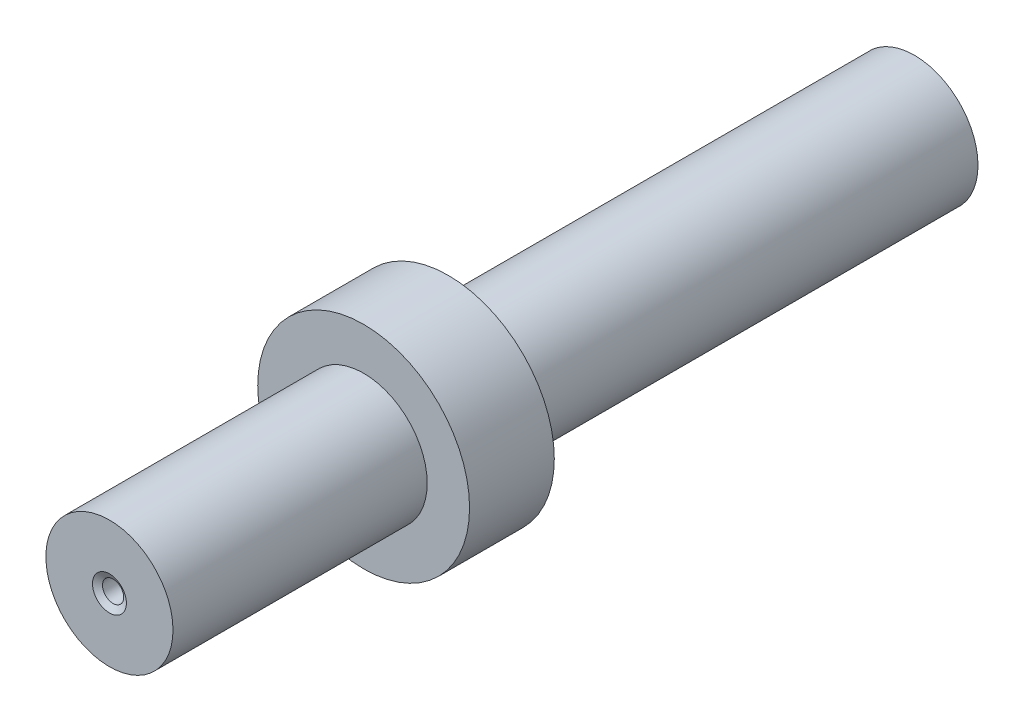
SolidWorks part; units mm, degrees
material "Chrome Stainless Steel"
ref_plane "Front Plane" through (0, 0, 0) normal (0, 0, 1) x (1, 0, 0)
ref_plane "Top Plane" through (0, 0, 0) normal (0, 1, 0) x (1, 0, 0)
ref_plane "Right Plane" through (0, 0, 0) normal (1, 0, 0) x (0, 0, -1)
sketch "Sketch1" plane through (0, 0, 0) normal (0, 0, 1) x (1, 0, 0)
  circle A0 centre (0, 0) radius 12.5
  dimension "D1" = 25
extrude "25mm dia" add sketch "Sketch1" along normal blind 10
sketch "Sketch2" plane through (0, 0, 10) normal (0, 0, 1) x (1, 0, 0)
  circle A0 centre (0, 0) radius 7.5
  dimension "D1" = 15
extrude "15mm dia bearing end" add sketch "Sketch2" along normal blind 40 from surface at -10 starting at face at (12.5, 0, 0)
sketch "Sketch3" plane through (0, 0, 0) normal (0, 0, -1) x (-1, 0, 0)
  circle A0 centre (0, 0) radius 7.5
  dimension "D1" = 15
extrude "15mm dia gear end" add sketch "Sketch3" along normal blind 55
hole_wizard "M3x0.5 Tapped Hole1" positions "Sketch6" profile "Sketch5" tap size "M3x0.5" standard "ANSI Metric"
sketch "Sketch6" plane through (0, 0, 40) normal (0, 0, 1) x (1, 0, 0)
  point P0 (0, 0)
sketch "Sketch5" plane through (0, 0, 40) normal (1, 0, 0) x (0, -1, 0)
  line L0 (0, 0) -> (0, 15.7511)
  line L1 (0, 15.7511) -> (1.25, 15)
  line L2 (1.25, 15) -> (1.25, 0.433)
  line L3 (1.25, 0.433) -> (2, 0)
  line L5 (2, 0) -> (0, 0)
  line L6 (-1.25, 0.433) -> (-2, 0) construction
  line L10 (0, 15.7511) -> (-1.25, 15) construction
  line L11 (0, -6.35) -> (0, 107.95) construction
  dimension "Tap Drill Dia." = 2.5
  dimension "Tap Drill Depth" = 15
  dimension "Near C'Sink Dia." = 4
  dimension "Near C'Sink Angle" = 120
  dimension "Drill Angle" = 118
cosmetic thread "Hole Thread1" parameters "D1"=12, "D2"=3
equation "\"a\"= 1"
equation "\"b\"= 1"
equation "\"c\"= 1"
equation "\"d\"= 1"
equation "\"e\"= 1"
equation "\"x\"= 1"
equation "\"y\"= 1"
equation "\"z\"= 1"
